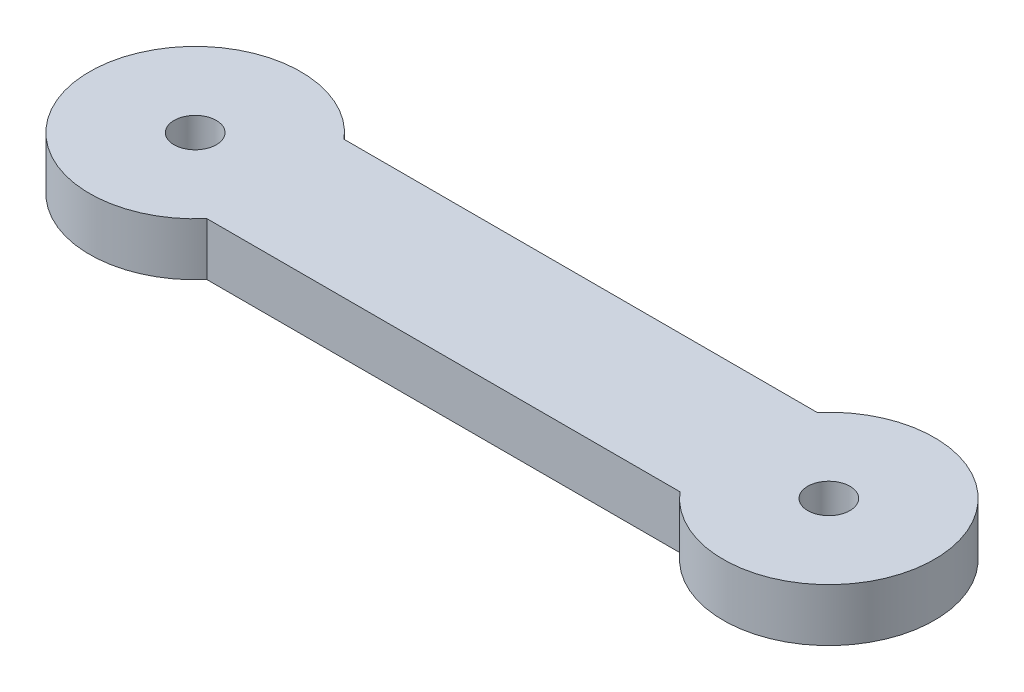
SolidWorks part; units mm, degrees
ref_plane "Ebene vorne" through (0, 0, 0) normal (0, 0, 1) x (1, 0, 0)
ref_plane "Ebene oben" through (0, 0, 0) normal (0, 1, 0) x (1, 0, 0)
ref_plane "Ebene rechts" through (0, 0, 0) normal (1, 0, 0) x (0, 0, -1)
sketch "Skizze1" plane through (0, 0, 0) normal (0, 1, 0) x (1, 0, 0)
  line L0 (0, 22.9671) -> (0, -13.5108) construction
  line L2 (0, 6.5) -> (30, 6.5)
  line L3 (30, 6.5) -> (30, 0)
  line L4 (-55, 0) -> (55, 0) construction
  line L5 (30, 0) -> (30, -6.5)
  line L6 (30, -6.5) -> (0, -6.5)
  line L7 (0, -6.5) -> (0, 6.5)
  circle A0 centre (30, 0) radius 10
  circle A1 centre (30, 0) radius 2
  dimension "D1" = 30
  dimension "D3" = 20
  dimension "D4" = 4
  dimension "D2" = 13
extrude "Aufsatz-Linear austragen1" add sketch "Skizze1" along normal blind 5 contours L6 A0 L2 L3 L5 | L2 A0 L6 L5 L3 | A0 L2 L7 L6
mirror "Spiegeln1" about plane through (0, 0, 0) normal (1, 0, 0) of "Aufsatz-Linear austragen1"
